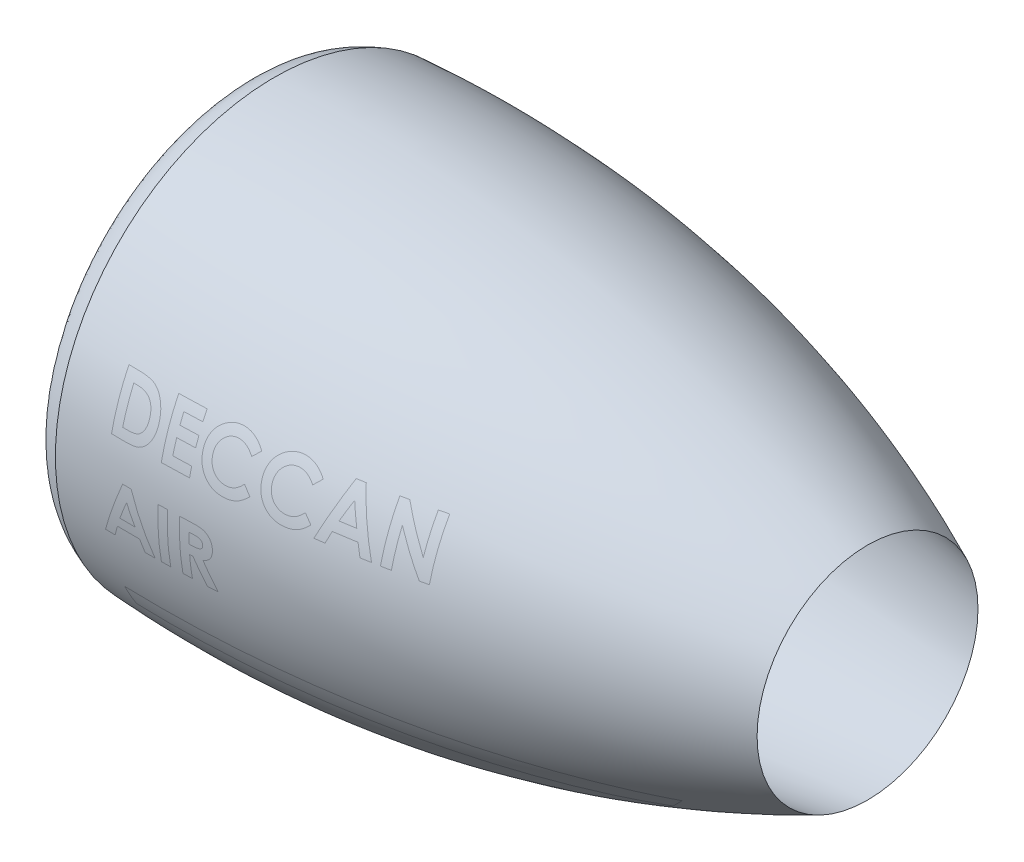
SolidWorks part; units mm, degrees
ref_plane "Front Plane" through (0, 0, 0) normal (0, 0, 1) x (1, 0, 0)
ref_plane "Top Plane" through (0, 0, 0) normal (0, 1, 0) x (1, 0, 0)
ref_plane "Right Plane" through (0, 0, 0) normal (1, 0, 0) x (0, 0, -1)
sketch "Sketch2" plane through (0, 0, 0) normal (0, 0, 1) x (1, 0, 0)
  line L0 (660.3933, 0) -> (0, 0) construction
  line L1 (0, 0) -> (0, 214.0962) construction
  line L2 (0, 180) -> (25, 180)
  line L3 (25, 180) -> (46.0856, 190)
  line L4 (46.0856, 190) -> (71.0856, 190)
  line L5 (580, 108) -> (71.0856, 190)
  spline S0 degree 2 poles (0, 214.0962) (307.1132, 232.7047) (580, 108) knots 0 0 0 1 1 1
  spline S1 degree 2 poles (0, 214.0962) (-44.1523, 199.1865) (0, 180) knots 0 0 0 1 1 1
  point P7 (0, 242.0557)
  point P12 (-22.0454, 198.752)
  point P13 (0, 214.0962)
  dimension "D1" = 580
  dimension "D2" = 108
  dimension "D3" = 180
  dimension "D4" = 190
  dimension "D5" = 25
  dimension "D6" = 25
revolve "Revolve1" add sketch "Sketch2" angle 360 about L0
ref_plane "Plane1" through (0, 0, 250) normal (0, 0, 1) x (1, 0, 0)
sketch "Sketch3" plane through (0, 0, 250) normal (0, 0, 1) x (1, 0, 0)
  line L0 (46.6631, 44.3515) -> (479.5335, 44.3515) construction
  line L1 (46.6631, -38.4156) -> (500.8222, -38.4156) construction
  line L2 (46.6631, -117.5232) -> (480.3339, -117.5232) construction
  line L3 (500.8222, -97.0349) -> (480.3339, -117.5232)
  line L4 (46.6631, -117.5232) -> (480.3339, -117.5232)
  line L5 (46.6631, -117.5232) -> (46.6631, -97.0349)
  line L6 (46.6631, -97.0349) -> (500.8222, -97.0349)
  text T0 "DECCAN" font "Century Gothic" height 50
  text T1 "AIR" font "Century Gothic" height 50
split line "Split Line2"
